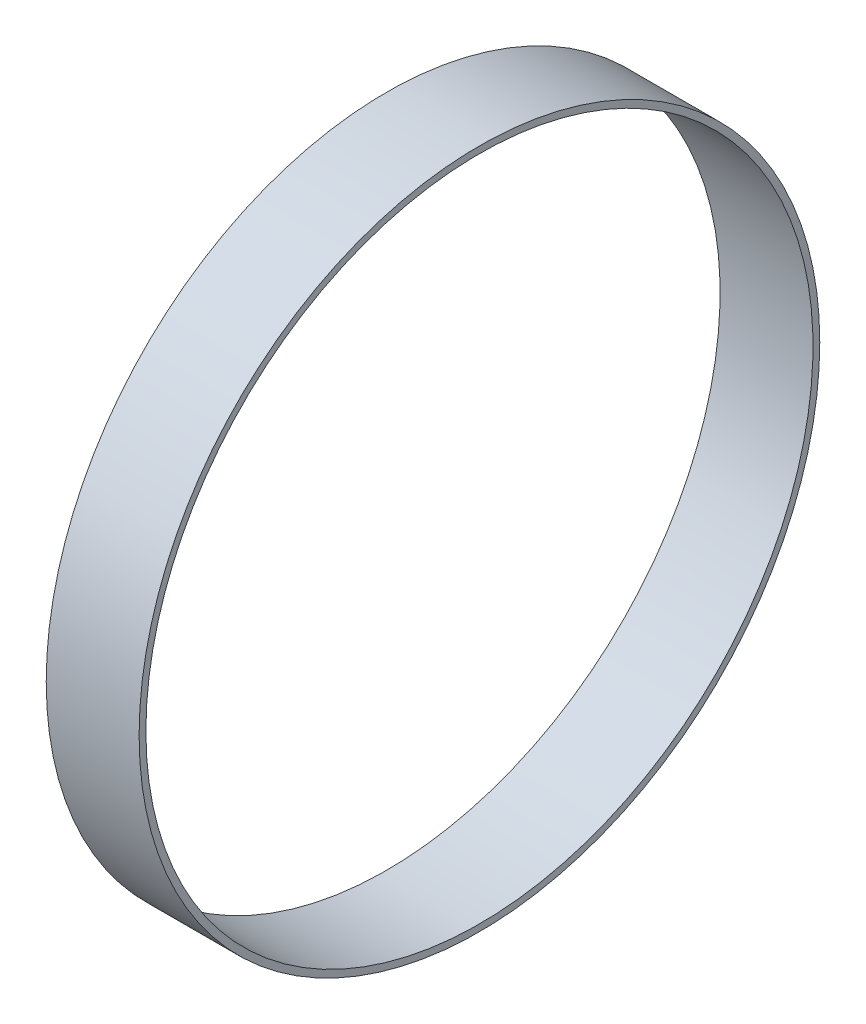
SolidWorks part; units mm, degrees
ref_plane "Plan1" through (0, 0, 0) normal (0, 0, 1) x (1, 0, 0)
ref_plane "Plan2" through (0, 0, 0) normal (0, 1, 0) x (1, 0, 0)
ref_plane "Plan3" through (0, 0, 0) normal (1, 0, 0) x (0, 0, -1)
sketch "Esquisse1" plane through (0, 0, 0) normal (0, 0, 1) x (1, 0, 0)
  line L0 (78.1, 50.2) -> (91.8, 50.2)
  line L1 (0, 0) -> (70, 0) construction
  line L2 (38.9, 0) -> (76.4, 0) construction
  line L3 (78.1, 43) -> (78.1, -43) construction
  line L4 (91.8, -43) -> (91.8, 43) construction
  dimension "D1" = 50.2
revolve "Base-Révol.-Mince" add sketch "Esquisse1" angle 360 about L1
